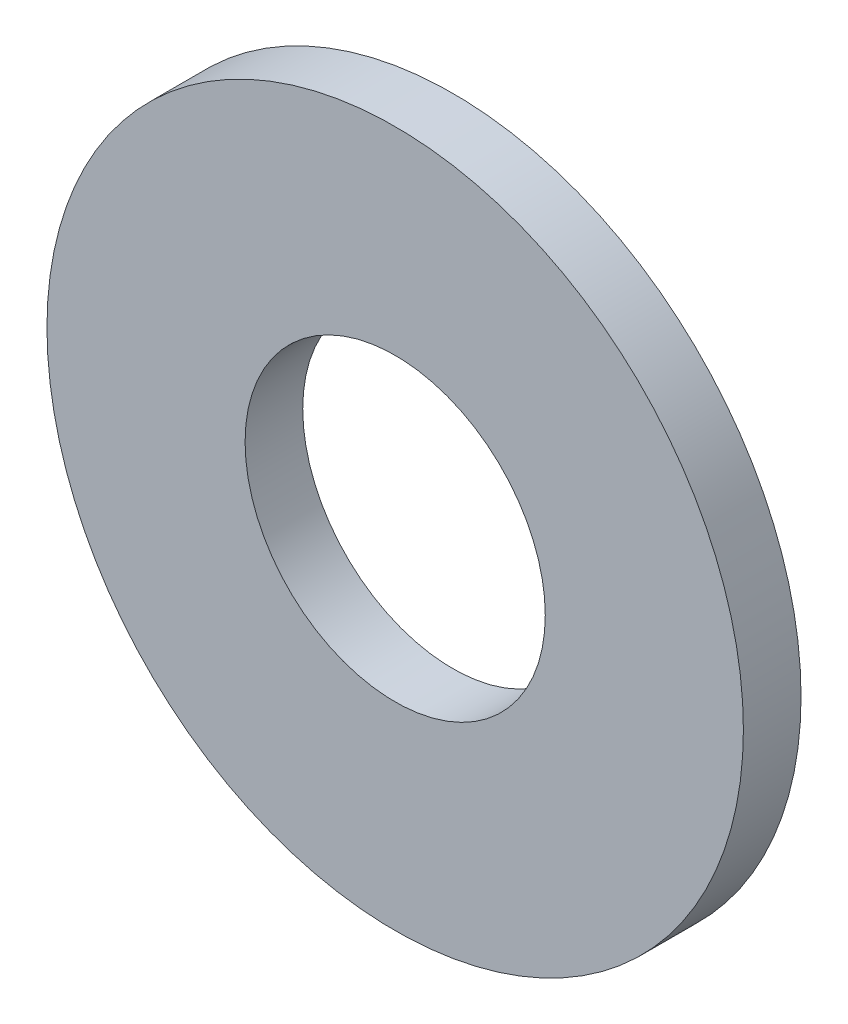
SolidWorks part; units mm, degrees
material "Простая углеродистая сталь"
ref_plane "Спереди" through (0, 0, 0) normal (0, 0, 1) x (1, 0, 0)
ref_plane "Сверху" through (0, 0, 0) normal (0, 1, 0) x (1, 0, 0)
ref_plane "Справа" through (0, 0, 0) normal (1, 0, 0) x (0, 0, -1)
sketch "Эскиз1" plane through (0, 0, 0) normal (0, 0, 1) x (1, 0, 0)
  circle A0 centre (0, 0) radius 14.5
  circle A1 centre (0, 0) radius 6.25
extrude "Бобышка-Вытянуть1" add sketch "Эскиз1" along normal blind 2.4
